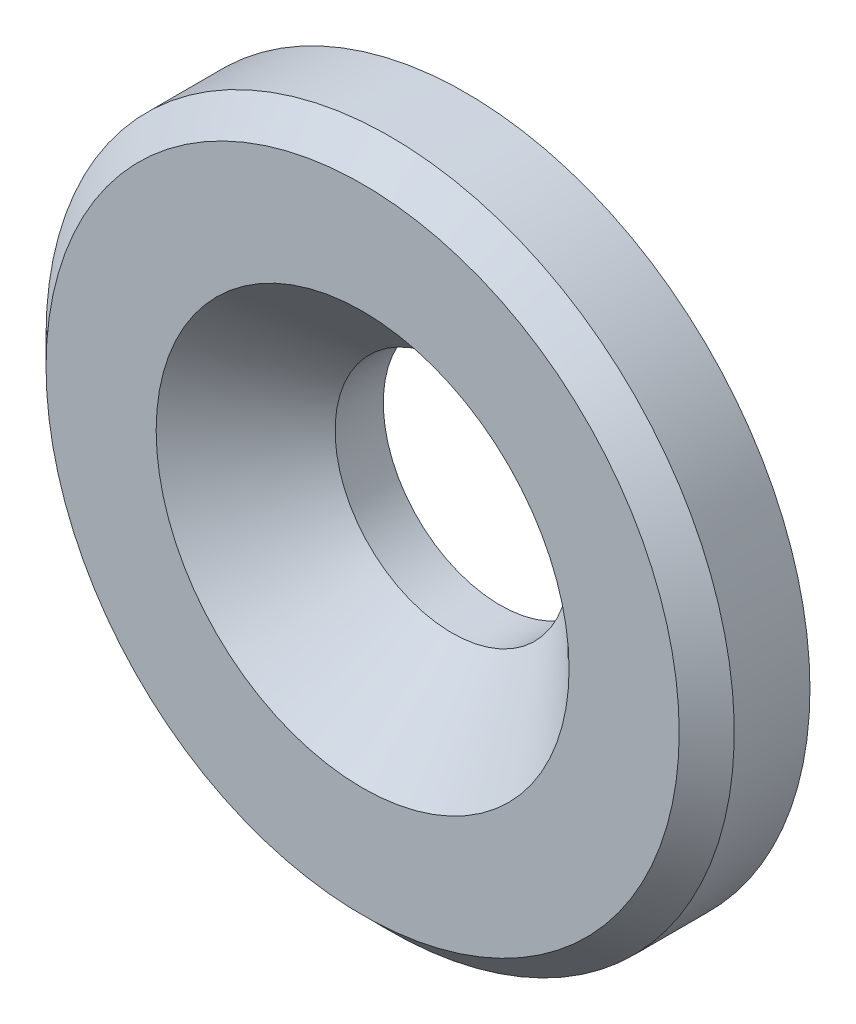
SolidWorks part; units mm, degrees
ref_plane "Front Plane" through (0, 0, 0) normal (0, 0, 1) x (1, 0, 0)
ref_plane "Top Plane" through (0, 0, 0) normal (0, 1, 0) x (1, 0, 0)
ref_plane "Right Plane" through (0, 0, 0) normal (1, 0, 0) x (0, 0, -1)
sketch "Sketch2" plane through (0, 0, 0) normal (0, 0, 1) x (1, 0, 0)
  circle A0 centre (0, 0) radius 3.5
extrude "Boss-Extrude1" add sketch "Sketch2" along normal blind 0.5
sketch "Sketch3" plane through (0, 0, 0.5) normal (0, 0, 1) x (1, 0, 0)
  circle A0 centre (0, 0) radius 5
extrude "Boss-Extrude2" add sketch "Sketch3" along normal blind 1.5
chamfer "Chamfer1" distance 0.4 angle 45 1 edges at (5, 0, 2)
sketch "Sketch4" plane through (0, 0, 0) normal (1, 0, 0) x (0, -1, 0)
  line L0 (3, -2) -> (0, -2)
  line L1 (0, -2) -> (0, 0)
  line L2 (3, -2) -> (1.7, -0.7)
  line L4 (1.7, -0.7) -> (1.7, 0)
  line L5 (1.7, 0) -> (0, 0)
  dimension "D1" = 1.8385
  dimension "D2" = 3
  dimension "D3" = 1.7
revolve "Cut-Revolve1" cut sketch "Sketch4" angle 360 about L1
